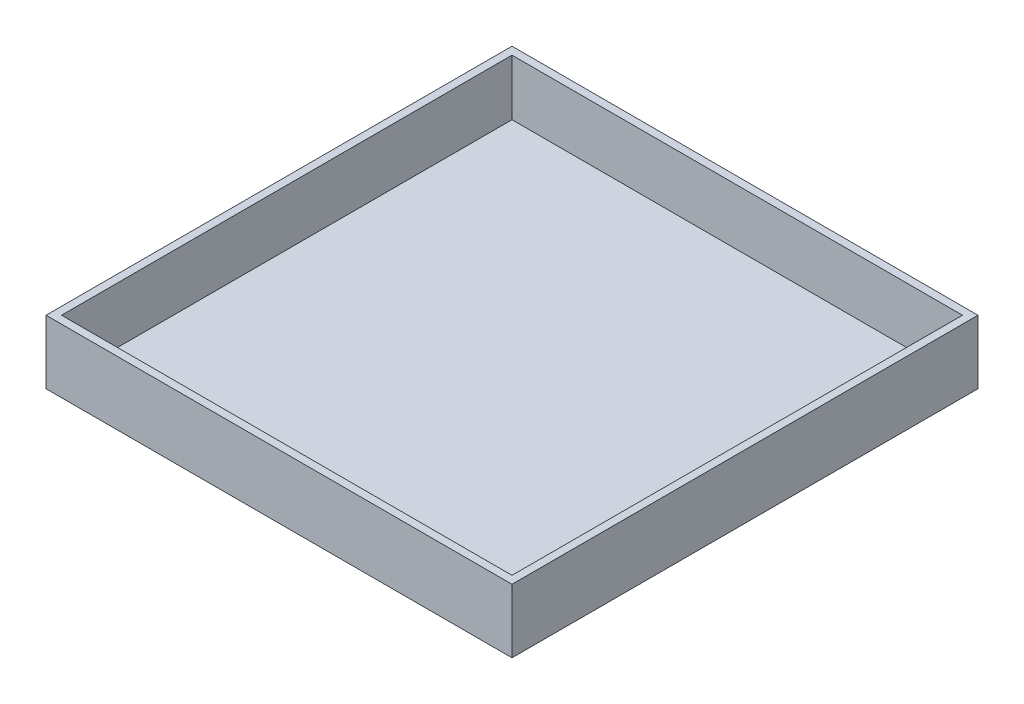
SolidWorks part; units mm, degrees
material "PVC Rigid"
ref_plane "Front Plane" through (0, 0, 0) normal (0, 0, 1) x (1, 0, 0)
ref_plane "Top Plane" through (0, 0, 0) normal (0, 1, 0) x (1, 0, 0)
ref_plane "Right Plane" through (0, 0, 0) normal (1, 0, 0) x (0, 0, -1)
sketch "Sketch1" plane through (0, 0, 0) normal (0, 1, 0) x (1, 0, 0)
  line L1 (-150, 150) -> (150, 150)
  line L2 (-150, 150) -> (-150, -150)
  line L3 (-150, -150) -> (150, -150)
  line L4 (150, 150) -> (150, -150)
  dimension "D1" = 300
  dimension "D2" = 300
  dimension "D3" = 150
  dimension "D4" = 150
extrude "Boss-Extrude1" add sketch "Sketch1" along normal blind 5
sketch "Sketch2" plane through (0, 5, 0) normal (0, 1, 0) x (1, 0, 0)
  line L1 (-150, 150) -> (150, 150)
  line L2 (-150, 150) -> (-150, -150)
  line L3 (-150, -150) -> (150, -150)
  line L4 (150, 150) -> (150, -150)
  line L5 (-145, 145) -> (145, 145)
  line L6 (-145, 145) -> (-145, -145)
  line L7 (-145, -145) -> (145, -145)
  line L8 (145, 145) -> (145, -145)
  dimension "D1" = 290
  dimension "D2" = 290
  dimension "D3" = 5
  dimension "D4" = 5
extrude "Boss-Extrude2" add sketch "Sketch2" along normal blind 36
